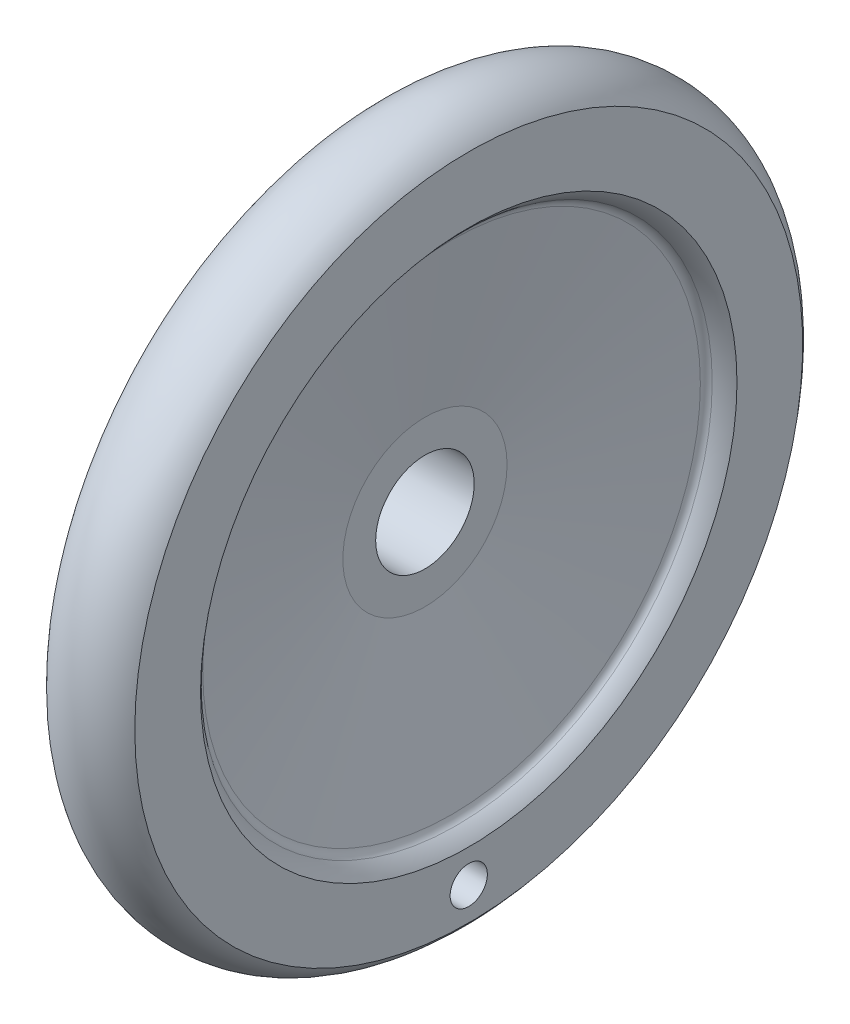
SolidWorks part; units mm, degrees
ref_plane "前视基准面" through (0, 0, 0) normal (0, 0, 1) x (1, 0, 0)
ref_plane "上视基准面" through (0, 0, 0) normal (0, 1, 0) x (1, 0, 0)
ref_plane "右视基准面" through (0, 0, 0) normal (1, 0, 0) x (0, 0, -1)
sketch "草图1" plane through (0, 0, 0) normal (0, 0, 1) x (1, 0, 0)
  line L0 (0, 0) -> (102.7154, 0) construction
  line L1 (55, 0) -> (-55, 0) construction
  line L2 (0, 49) -> (0, 61)
  line L3 (0, -55) -> (0, 55) construction
  line L4 (-12, 45.8348) -> (-16.0879, 20.2123)
  line L5 (-21.0254, 16) -> (-35, 16)
  line L6 (-35, 16) -> (-35, 9)
  line L7 (-35, 9) -> (-8, 9)
  line L8 (-8, 9) -> (-8, 15)
  line L9 (-8, 15) -> (-3, 46.3397)
  arc A0 (0, 61) -> (-12, 45.8348) centre (-8, 55) ccw
  arc A1 (0, 49) -> (0, 61) centre (-8, 55) ccw construction
  arc A2 (-12, 45.8348) -> (-3, 46.3397) centre (-8, 55) ccw construction
  arc A3 (-3, 46.3397) -> (0, 49) centre (-8, 55) ccw
  arc A4 (-16.0879, 20.2123) -> (-21.0254, 16) centre (-21.0254, 21) cw
  point P10 (-6.0104, 55)
  point P13 (0, 28.148)
  point P19 (-7.388, 45.0954)
  point P20 (-17.2522, 15)
  point P21 (-16.2059, 47.667)
  point P22 (-21, 16)
  point P23 (-3, 47.769)
  point P24 (-16.2427, 47.2231)
  point P25 (-8.4306, 55)
  dimension "D1" = 20
  dimension "D7" = 130
  dimension "D10" = 18
  dimension "D11" = 5
  dimension "D2" = 12
  dimension "D3" = 3
  dimension "D4" = 32
  dimension "D5" = 18
  dimension "D6" = 30
  dimension "D8" = 8
  dimension "D9" = 35
revolve "旋转1" add sketch "草图1" angle 360 about L0
sketch "草图2" plane through (0, 0, 0) normal (0, 1, 0) x (1, 0, 0)
  line L0 (-71.5, 0) -> (71.5, 0) construction
  line L1 (-35, 16) -> (-35, -16) construction
  circle A0 centre (-26, 0) radius 4
  dimension "D1" = 8
  dimension "D2" = 9
extrude "切除-拉伸1" cut sketch "草图2" against normal through all both and the other way through all
chamfer "倒角1" distance 1 angle 45 1 edges at (-35, 0, 9)
fillet "圆角1" radius 2 2 edges at (-3, 0, 46.3397) (-12, 0, 45.8348)
sketch "草图3" plane through (0, 0, 0) normal (1, 0, 0) x (0, 0, -1)
  line L0 (0, 19.25) -> (0, -19.25) construction
  circle A0 centre (0, 0) radius 65 construction
  point P0 (0, -55)
  dimension "D1" = 10
hole_wizard "M8 螺纹孔的螺纹孔钻头1" positions "草图3" profile "草图4" hole size "M8" standard "GB" end condition through all
sketch "草图4" plane through (0, -55, 0) normal (0, 1, 0) x (0, 0, -1)
  line L0 (0, 0) -> (0, 35)
  line L1 (0, 35) -> (3.4, 35)
  line L2 (3.4, 35) -> (3.4, 0)
  line L5 (3.4, 0) -> (0, 0)
  line L11 (0, -6.35) -> (0, 107.95) construction
  dimension "通孔孔直径" = 6.8
  dimension "通孔孔深度" = 35
